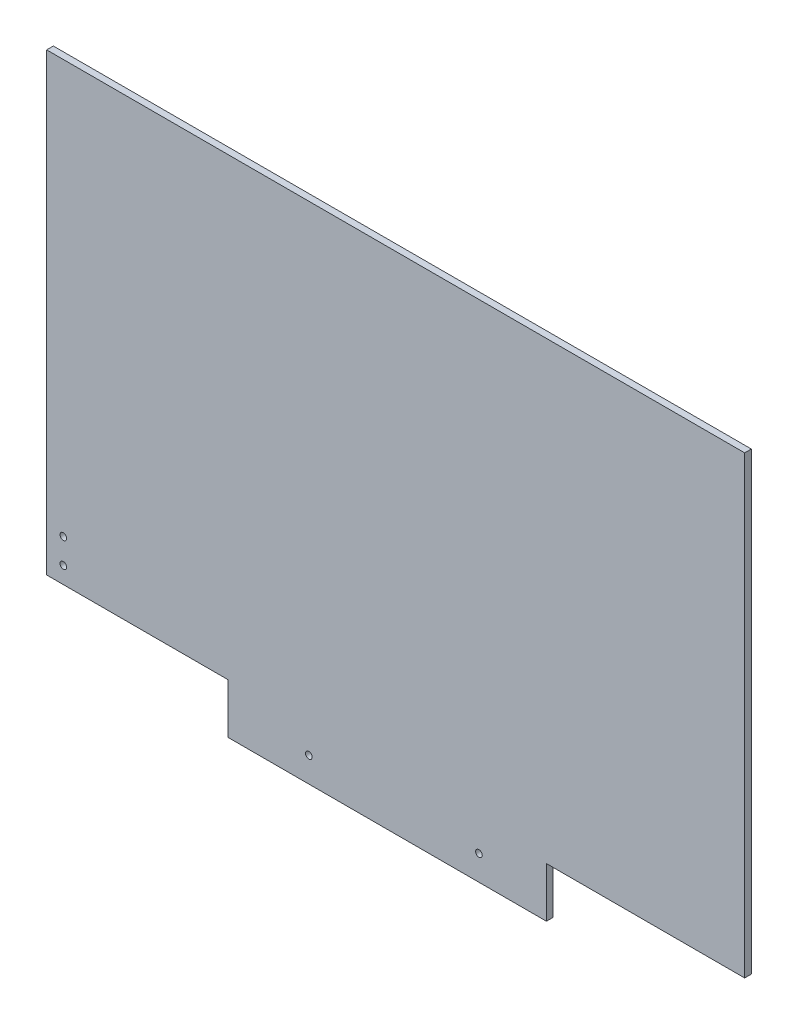
SolidWorks part; units mm, degrees
ref_plane "Front Plane" through (0, 0, 0) normal (0, 0, 1) x (1, 0, 0)
ref_plane "Top Plane" through (0, 0, 0) normal (0, 1, 0) x (1, 0, 0)
ref_plane "Right Plane" through (0, 0, 0) normal (1, 0, 0) x (0, 0, -1)
sketch "Sketch1" plane through (0, 0, 0) normal (0, 0, 1) x (1, 0, 0)
  line L1 (-209.5, 151.5) -> (209.5, 151.5)
  line L2 (-209.5, 151.5) -> (-209.5, -151.5)
  line L3 (-209.5, -151.5) -> (209.5, -151.5)
  line L4 (209.5, 151.5) -> (209.5, -151.5)
  line L5 (-209.5, 151.5) -> (209.5, -151.5) construction
  line L6 (-209.5, -151.5) -> (209.5, 151.5) construction
  point P0 (0, 0)
  dimension "D1" = 419
  dimension "D2" = 303
extrude "Boss-Extrude1" add sketch "Sketch1" along normal blind 4
sketch "Sketch2" plane through (0, 0, 0) normal (0, 0, -1) x (-1, 0, 0)
  line L0 (-209.5, -121.5) -> (-90.5, -121.5)
  line L1 (-209.5, -151.5) -> (-209.5, 151.5) construction
  line L2 (-90.5, -121.5) -> (-90.5, -151.5)
  line L3 (209.5, -151.5) -> (-209.5, -151.5) construction
  line L4 (209.5, -121.5) -> (100.5, -121.5)
  line L5 (209.5, 151.5) -> (209.5, -151.5) construction
  line L6 (100.5, -121.5) -> (100.5, -151.5)
  line L7 (-209.5, -121.5) -> (-209.5, -151.5)
  line L8 (-209.5, -151.5) -> (-90.5, -151.5)
  line L9 (209.5, -121.5) -> (209.5, -151.5)
  line L10 (209.5, -151.5) -> (100.5, -151.5)
  dimension "D1" = 30
  dimension "D2" = 90.5
  dimension "D3" = 100.5
extrude "Cut-Extrude1" cut sketch "Sketch2" against normal blind 4
sketch "Sketch3" plane through (0, 0, 0) normal (0, 0, -1) x (-1, 0, 0)
  line L0 (100.5, -151.5) -> (-90.5, -151.5) construction
  circle A0 centre (-49.9836, -136.5) radius 2
  circle A1 centre (52.1258, -136.5) radius 2
  dimension "D1" = 4
  dimension "D2" = 4
  dimension "D3" = 15
  dimension "D4" = 15
extrude "Cut-Extrude2" cut sketch "Sketch3" against normal through all
sketch "Sketch4" plane through (0, 0, 0) normal (0, 0, -1) x (-1, 0, 0)
  line L0 (209.5, -121.5) -> (100.5, -121.5) construction
  line L1 (209.5, 151.5) -> (209.5, -121.5) construction
  circle A0 centre (199.5, -111.5) radius 2
  circle A1 centre (199.5, -96.5) radius 2
  dimension "D1" = 4
  dimension "D2" = 4
  dimension "D3" = 10
  dimension "D4" = 25
  dimension "D5" = 10
  dimension "D6" = 10
extrude "Cut-Extrude3" cut sketch "Sketch4" against normal through all
